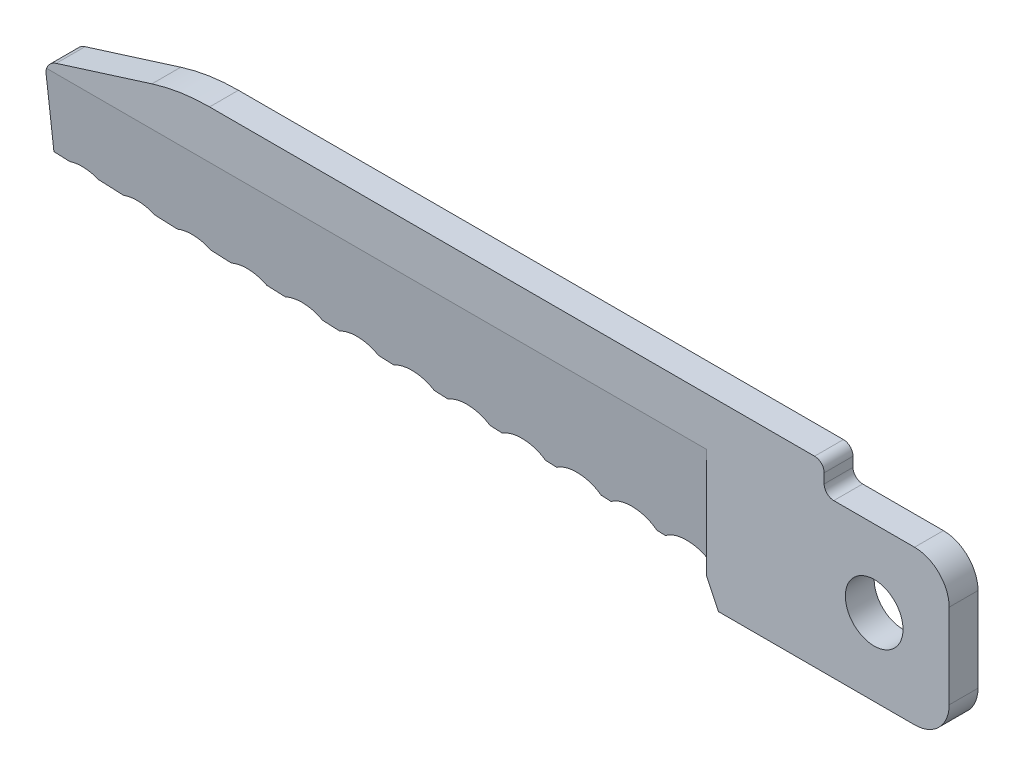
SolidWorks part; units mm, degrees
ref_plane "Front Plane" through (0, 0, 0) normal (0, 0, 1) x (1, 0, 0)
ref_plane "Top Plane" through (0, 0, 0) normal (0, 1, 0) x (1, 0, 0)
ref_plane "Right Plane" through (0, 0, 0) normal (1, 0, 0) x (0, 0, -1)
sketch "Sketch1" plane through (0, 0, 0) normal (0, 0, 1) x (1, 0, 0)
  line L0 (0, 3) -> (0, 6.7128)
  line L1 (0.5601, 7.476) -> (5.5362, 9.0399)
  line L2 (8.5344, 9.5) -> (40, 9.5)
  line L3 (40.5, 9) -> (40.5, 8.5)
  line L4 (41, 8) -> (47, 8)
  line L5 (47, 8) -> (47, 0)
  line L6 (47, 0) -> (35, 0)
  line L7 (35, 0) -> (34.3842, 1.3)
  line L8 (34.3842, 1.3) -> (0, 3)
  line L9 (34.3842, 1.3) -> (30.5, 9.5)
  arc A0 (0.5601, 7.476) -> (0, 6.7128) centre (0.8, 6.7128) ccw
  arc A1 (8.5344, 9.5) -> (5.5362, 9.0399) centre (8.5344, -0.5) ccw
  arc A2 (41, 8) -> (40.5, 8.5) centre (41, 8.5) cw
  arc A3 (40.5, 9) -> (40, 9.5) centre (40, 9) ccw
  point P11 (0, 7.3)
  point P15 (7, 9.5)
  point P18 (40.5, 8)
  point P22 (40.5, 9.5)
  dimension "D11" = 0.8
  dimension "D12" = 10
  dimension "D13" = 0.5
  dimension "D1" = 2.2
  dimension "D2" = 8.2
  dimension "D3" = 1.5
  dimension "D4" = 12
  dimension "D5" = 8
  dimension "D6" = 6.5
  dimension "D7" = 6.5
  dimension "D8" = 47
  dimension "D9" = 40
  dimension "D10" = 10
extrude "Boss-Extrude1" add sketch "Sketch1" along normal mid plane 1.5 contours L2 A1 L1 A0 L0 L8 L9 | L3 A3 L2 L9 L7 L6 L5 L4 A2
fillet "Fillet1" radius 1.8 2 edges at (47, 0, 0) (47, 8, 0)
sketch "Sketch2" plane through (0, 0, -0.75) normal (0, 0, -1) x (-1, 0, 0)
  line L0 (-30.5, 8.5) -> (-16.5, 8.5)
  line L1 (-8.5344, 9.5) -> (-40, 9.5) construction
  line L2 (-40.5, 9) -> (-40.5, 8.5) construction
  arc A1 (-30.5, 8.5) -> (-16.5, 8.5) centre (-23.5, 38.6993) ccw
  point P8 (-19.7234, -25.7567)
  point P9 (-20.5418, 35.4707)
  point P10 (0, 0)
  point P11 (0, 0)
  dimension "D4" = 62
  dimension "D1" = 14
  dimension "D2" = 1
  dimension "D3" = 10
ref_plane "Plane1" through (34.3842, 0, 0) normal (1, 0, 0) x (0, 0, -1)
sketch "Sketch4" plane through (34.3842, 0, 0) normal (1, 0, 0) x (0, 0, -1)
  line L0 (-0.75, 1.3) -> (-0.125, 1.3)
  line L1 (-0.75, 6.2) -> (-0.75, 1.8) construction
  line L2 (-0.125, 1.3) -> (-0.75, 7)
  line L3 (-0.75, 7) -> (-0.75, 1.3)
  line L4 (0, 0) -> (0, 7.2378) construction
  line L5 (0.75, 1.3) -> (0.125, 1.3)
  line L6 (0.75, 7) -> (0.75, 1.3)
  line L7 (0.125, 1.3) -> (0.75, 7)
  line L8 (0.75, 0) -> (-0.75, 0) construction
  dimension "D1" = 0.25
  dimension "D2" = 1.3
  dimension "D3" = 5.7
extrude "Cut-Extrude3" cut sketch "Sketch4" against normal through all
sketch "Sketch7" plane through (34.3842, 0, 0) normal (1, 0, 0) x (0, 0, -1)
  line L0 (-0.1855, 1.8515) -> (-0.75, 1.3)
  line L2 (-0.125, 1.3) -> (-0.75, 7) construction
  point P2 (-0.1855, 1.8515)
sketch "Sketch5" plane through (0, 0.0019, 0.0173) normal (0, -0.109, -0.994) x (-1, 0, 0)
  line L1 (-34.3842, 0.825) -> (-34.3842, -0.825) construction
  line L2 (-34.3842, 1.3059) -> (0, 3.0161) construction
  circle A0 centre (-32.7842, 0.6345) radius 1.6
  dimension "D2" = 3.2
  dimension "D1" = 1.6
  dimension "D3" = 0.75
extrude "Cut-Extrude4" cut sketch "Sketch5" along direction (0, -0.6988, 0.7153) on the side against the normal blind 20.5
pattern_linear "LPattern1" count 12 spacing 2.85 along (-0.9988, 0.0494, -0.0054) of "Cut-Extrude4"
sketch "Sketch8" plane through (0, 0, 0.75) normal (0, 0, 1) x (1, 0, 0)
  line L0 (45.2, 0) -> (35, 0) construction
  line L1 (41, 8) -> (45.2, 8) construction
  circle A0 centre (43.1, 4) radius 1.5
  point P6 (43.1, 8)
  dimension "D1" = 3
  dimension "D2" = 4
extrude "Cut-Extrude5" cut sketch "Sketch8" against normal blind 20.5
revolve "Cut-Revolve1" cut sketch "Sketch2" angle 90 about L0
